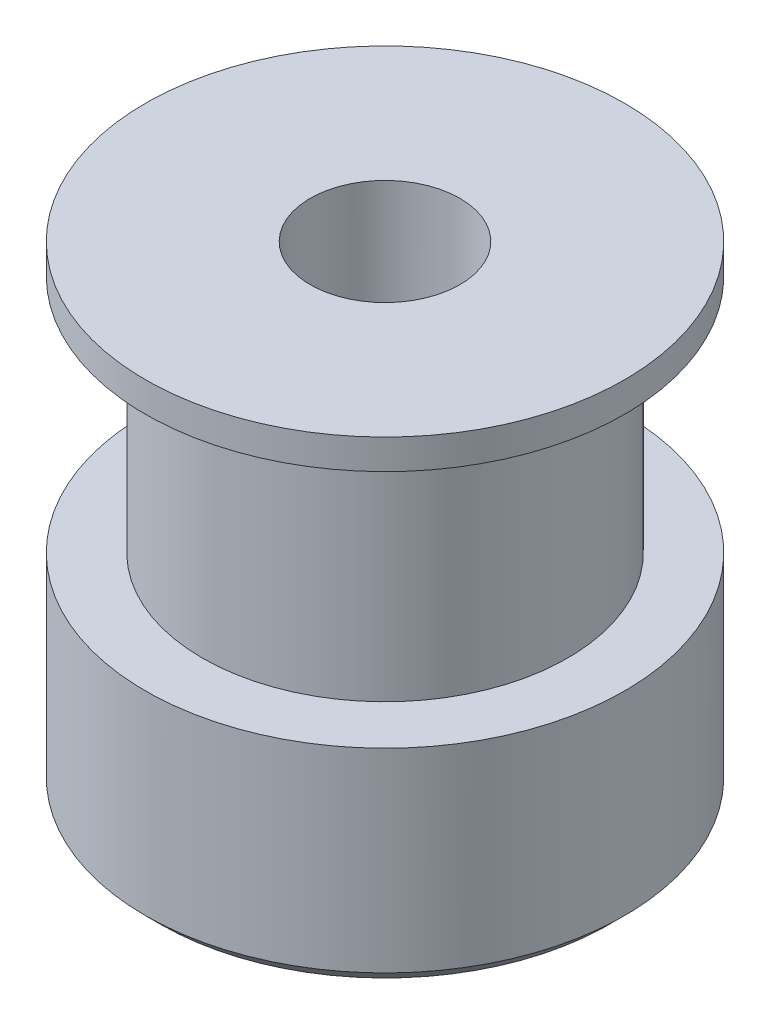
SolidWorks part; units mm, degrees
ref_plane "Front Plane" through (0, 0, 0) normal (0, 0, 1) x (1, 0, 0)
ref_plane "Top Plane" through (0, 0, 0) normal (0, 1, 0) x (1, 0, 0)
ref_plane "Right Plane" through (0, 0, 0) normal (1, 0, 0) x (0, 0, -1)
sketch "Sketch1" plane through (0, 0, 0) normal (0, 0, 1) x (1, 0, 0)
  line L0 (-2.5, 0) -> (-2.5, 16)
  line L1 (-2.5, 16) -> (-8, 16)
  line L2 (-8, 16) -> (-8, 15)
  line L3 (-8, 15) -> (-6.1, 15)
  line L4 (-6.1, 15) -> (-6.1, 7)
  line L5 (-6.1, 7) -> (-8, 7)
  line L8 (-8, 7) -> (-8, 0)
  line L9 (-8, 0) -> (-2.5, 0)
  line L10 (0, 0) -> (0, 23.1903) construction
  line L11 (0, 0) -> (-4.875, 0) construction
  dimension "D1" = 16
  dimension "D2" = 5
  dimension "D3" = 12.2
  dimension "D4" = 16
  dimension "D5" = 16
  dimension "D6" = 1
  dimension "D7" = 7
revolve "Revolve1" add sketch "Sketch1" angle 360 about L10
chamfer "Chamfer1" distance 0.5 angle 45 1 edges at (0, 0, -8)
sketch "Sketch2" plane through (0, 0, 0) normal (0, 0, 1) x (1, 0, 0)
  line L0 (0, 7) -> (0, 0) construction
  line L1 (8, 7) -> (-8, 7) construction
  circle A0 centre (0, 3.5) radius 1.5
  dimension "D1" = 3
extrude "Cut-Extrude1" cut sketch "Sketch2" against normal up to next
sketch "Sketch3" plane through (0, 0, 0) normal (1, 0, 0) x (0, 0, -1)
  line L0 (0, 0) -> (0, 7) construction
  line L1 (8, 7) -> (-8, 7) construction
  circle A0 centre (0, 3.5) radius 1.5
  dimension "D1" = 3
extrude "Cut-Extrude2" cut sketch "Sketch3" against normal up to next
